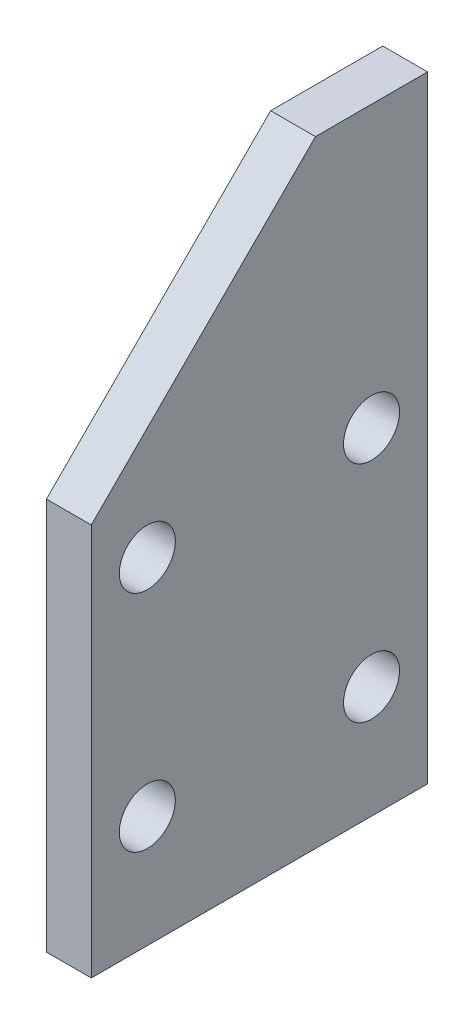
SolidWorks part; units mm, degrees
ref_plane "Спереди" through (0, 0, 0) normal (0, 0, 1) x (1, 0, 0)
ref_plane "Сверху" through (0, 0, 0) normal (0, 1, 0) x (1, 0, 0)
ref_plane "Справа" through (0, 0, 0) normal (1, 0, 0) x (0, 0, -1)
sketch "Эскиз1" plane through (0, 0, 0) normal (1, 0, 0) x (0, 0, -1)
  line L0 (0, 30) -> (30, 30) construction
  line L1 (0, 0) -> (30, 0)
  line L2 (0, 0) -> (0, 35)
  line L3 (20, 55) -> (30, 55)
  line L4 (30, 0) -> (30, 55)
  line L5 (0, 10) -> (30, 10) construction
  line L6 (0, 20) -> (30, 20) construction
  line L7 (0, 35) -> (20, 55)
  circle A0 centre (5, 10) radius 2.5
  circle A1 centre (25, 10) radius 2.5
  circle A2 centre (5, 30) radius 2.5
  circle A3 centre (25, 30) radius 2.5
  dimension "D5" = 5
  dimension "D1" = 30
  dimension "D2" = 55
  dimension "D3" = 10
  dimension "D4" = 20
  dimension "D6" = 20
  dimension "D7" = 5
  dimension "D8" = 20
  dimension "D9" = 20
  dimension "D10" = 15
  dimension "D11" = 20
extrude "Бобышка-Вытянуть1" add sketch "Эскиз1" along normal blind 4
